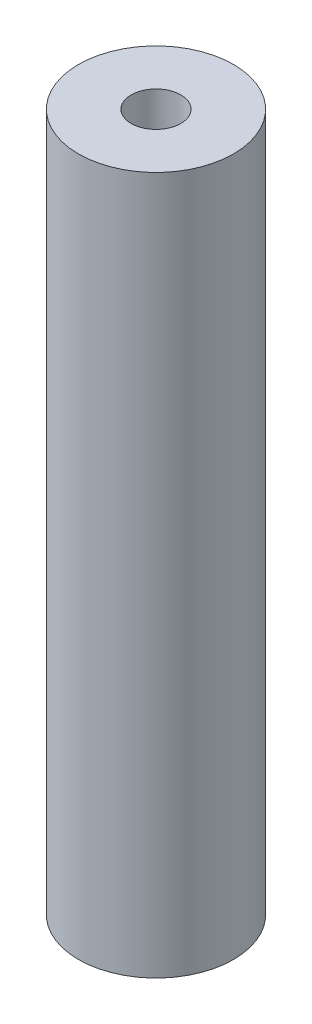
SolidWorks part; units mm, degrees
ref_plane "Front Plane" through (0, 0, 0) normal (0, 0, 1) x (1, 0, 0)
ref_plane "Top Plane" through (0, 0, 0) normal (0, 1, 0) x (1, 0, 0)
ref_plane "Right Plane" through (0, 0, 0) normal (1, 0, 0) x (0, 0, -1)
sketch "Sketch1" plane through (0, 0, 0) normal (0, 1, 0) x (1, 0, 0)
  circle A2 centre (0, 0) radius 1.6
  circle A3 centre (0, 0) radius 5
extrude "Boss-Extrude1" add sketch "Sketch1" along normal blind 45
